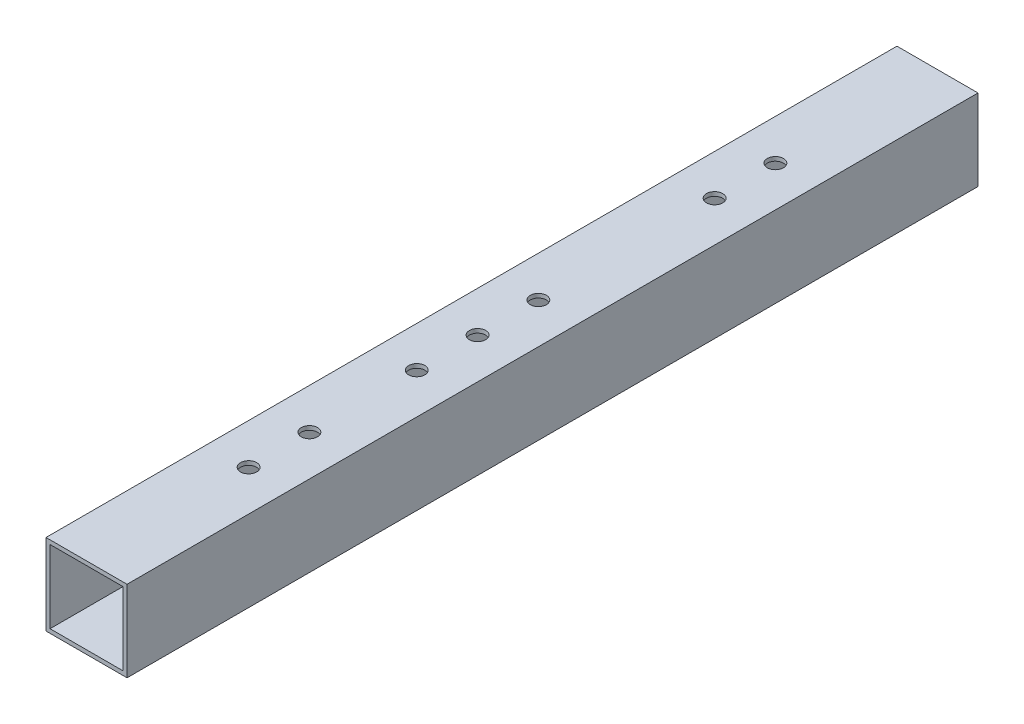
SolidWorks part; units mm, degrees
ref_plane "前视基准面" through (0, 0, 0) normal (0, 0, 1) x (1, 0, 0)
ref_plane "上视基准面" through (0, 0, 0) normal (0, 1, 0) x (1, 0, 0)
ref_plane "右视基准面" through (0, 0, 0) normal (1, 0, 0) x (0, 0, -1)
other "Configuration Table"
sketch "草图1" plane through (0, 0, 0) normal (0, 0, 1) x (1, 0, 0)
  line L1 (-10, -10) -> (10, -10)
  line L2 (-10, -10) -> (-10, 10)
  line L3 (-10, 10) -> (10, 10)
  line L4 (10, -10) -> (10, 10)
  line L5 (-10, -10) -> (10, 10) construction
  line L6 (-10, 10) -> (10, -10) construction
  line L7 (-9, 9) -> (9, 9)
  line L8 (-9, 9) -> (-9, -9)
  line L9 (-9, -9) -> (9, -9)
  line L10 (9, 9) -> (9, -9)
  line L11 (-9, 9) -> (9, -9) construction
  line L12 (-9, -9) -> (9, 9) construction
  point P0 (0, 0)
  point P5 (0, 0)
  dimension "D1" = 20
  dimension "D2" = 18
extrude "凸台-拉伸1" add sketch "草图1" along normal mid plane 210
sketch "草图2" plane through (0, 10, 0) normal (0, 1, 0) x (1, 0, 0)
  line L0 (0, -1000) -> (0, 49000) construction
  line L1 (10, -105) -> (-10, -105) construction
  line L2 (10, 105) -> (-10, 105) construction
  circle A0 centre (0, 65) radius 2
  circle A1 centre (0, -65) radius 2
  circle A2 centre (0, -50) radius 2
  circle A3 centre (0, 50) radius 2
  dimension "D1" = 4
  dimension "D2" = 4
  dimension "D3" = 4
  dimension "D4" = 4
  dimension "D5" = 15
  dimension "D6" = 15
  dimension "D7" = 40
  dimension "D8" = 40
extrude "切除-拉伸1" cut sketch "草图2" against normal through all
sketch "草图3" plane through (0, 10, 0) normal (0, 1, 0) x (1, 0, 0)
  line L0 (0, -1000) -> (0, 49000) construction
  line L1 (10, -105) -> (-10, -105) construction
  circle A0 centre (0, -8.5) radius 2
  circle A1 centre (0, 6.5) radius 2
  circle A2 centre (0, -23.5) radius 2
  dimension "D1" = 4
  dimension "D2" = 96.5
  dimension "D3" = 4
  dimension "D4" = 4
  dimension "D5" = 15
  dimension "D6" = 15
extrude "切除-拉伸2" cut sketch "草图3" against normal through all
